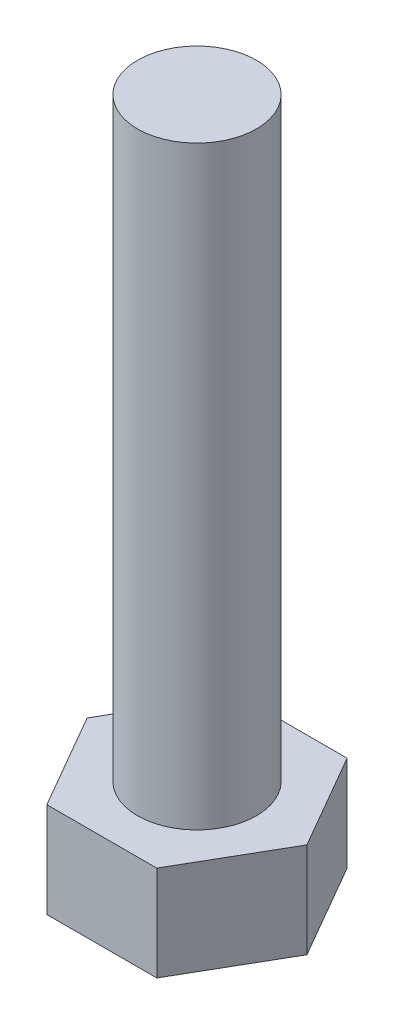
SolidWorks part; units mm, degrees
ref_plane "Front Plane" through (0, 0, 0) normal (0, 0, 1) x (1, 0, 0)
ref_plane "Top Plane" through (0, 0, 0) normal (0, 1, 0) x (1, 0, 0)
ref_plane "Right Plane" through (0, 0, 0) normal (1, 0, 0) x (0, 0, -1)
sketch "Sketch1" plane through (0, 0, 0) normal (0, 1, 0) x (1, 0, 0)
  line L1 (4.6188, 0) -> (2.3094, 4)
  line L2 (2.3094, 4) -> (-2.3094, 4)
  line L3 (-2.3094, 4) -> (-4.6188, 0)
  line L4 (-4.6188, 0) -> (-2.3094, -4)
  line L5 (-2.3094, -4) -> (2.3094, -4)
  line L6 (2.3094, -4) -> (4.6188, 0)
  circle A0 centre (0, 0) radius 4 construction
extrude "Boss-Extrude1" add sketch "Sketch1" along normal blind 4
sketch "Sketch2" plane through (0, 4, 0) normal (0, 1, 0) x (1, 0, 0)
  circle A0 centre (0, 0) radius 2.5
extrude "Boss-Extrude2" add sketch "Sketch2" along normal blind 25
